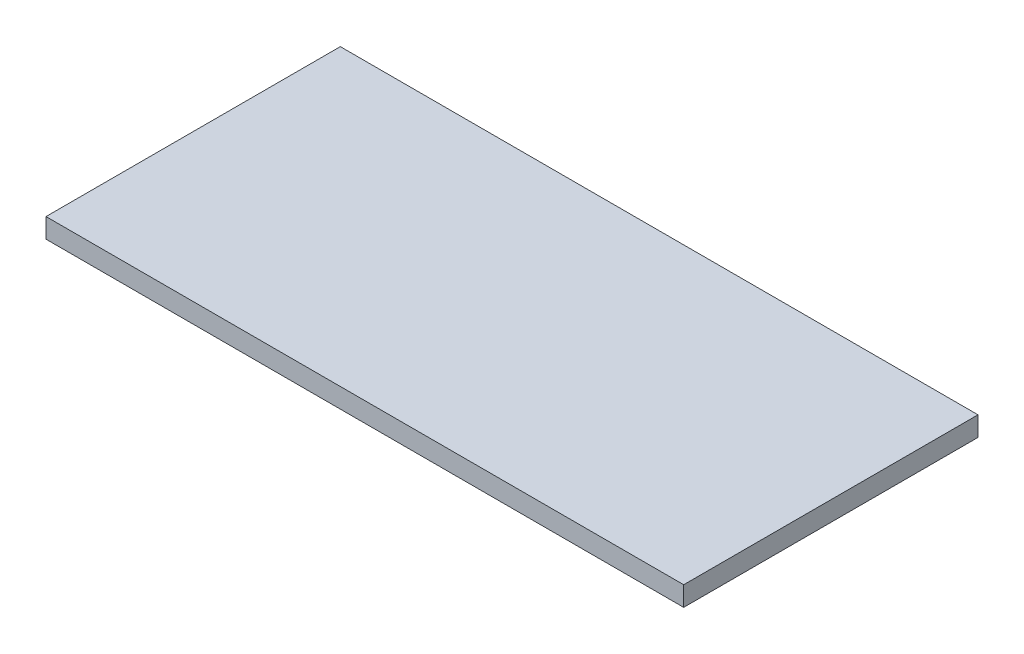
SolidWorks part; units mm, degrees
ref_plane "Front Plane" through (0, 0, 0) normal (0, 0, 1) x (1, 0, 0)
ref_plane "Top Plane" through (0, 0, 0) normal (0, 1, 0) x (1, 0, 0)
ref_plane "Right Plane" through (0, 0, 0) normal (1, 0, 0) x (0, 0, -1)
sketch "Sketch1" plane through (0, 0, 0) normal (0, 1, 0) x (1, 0, 0)
  line L1 (0, 0) -> (-65, 0)
  line L2 (0, 0) -> (0, -30)
  line L3 (0, -30) -> (-65, -30)
  line L4 (-65, 0) -> (-65, -30)
extrude "Boss-Extrude1" add sketch "Sketch1" along normal blind 2
